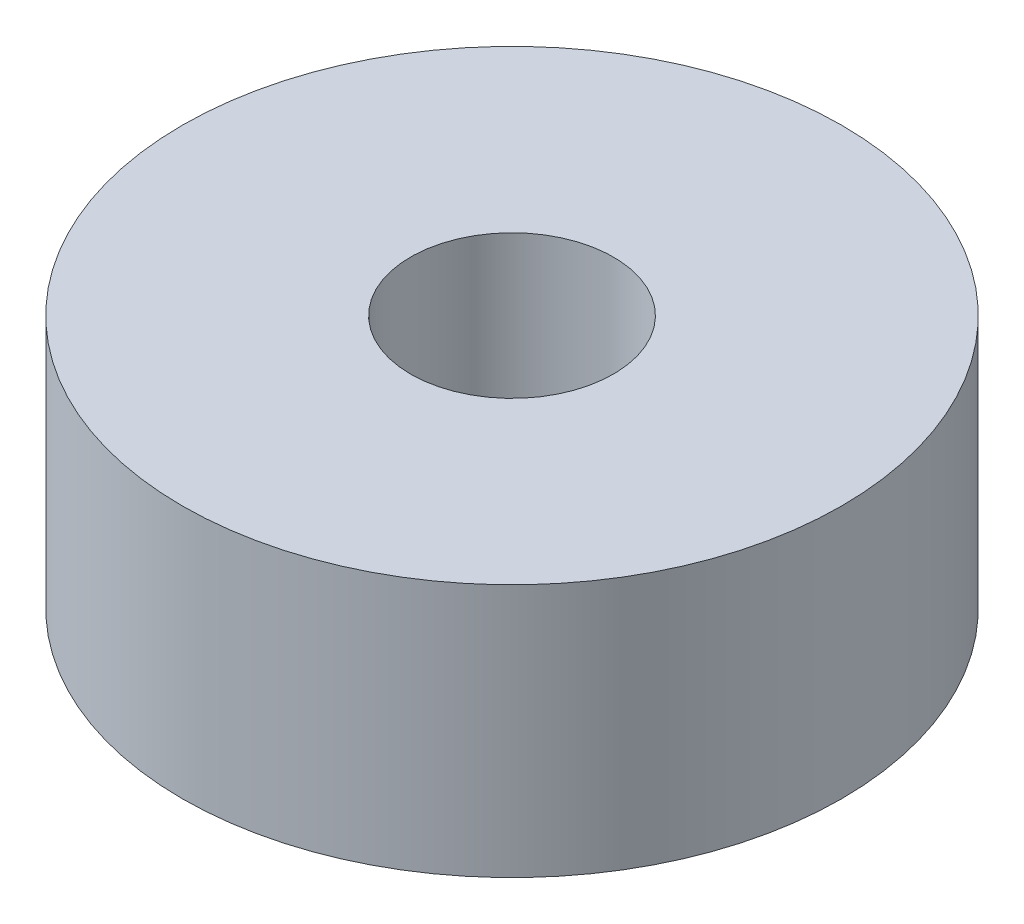
SolidWorks part; units mm, degrees
ref_plane "Plan de face" through (0, 0, 0) normal (0, 0, 1) x (1, 0, 0)
ref_plane "Plan de dessus" through (0, 0, 0) normal (0, 1, 0) x (1, 0, 0)
ref_plane "Plan de droite" through (0, 0, 0) normal (1, 0, 0) x (0, 0, -1)
sketch "Esquisse1" plane through (0, 0, 0) normal (0, 1, 0) x (1, 0, 0)
  circle A0 centre (0, 0) radius 2
  circle A1 centre (0, 0) radius 6.5
  dimension "D1" = 13
  dimension "D2" = 4
extrude "Boss.-Extru.1" add sketch "Esquisse1" along normal blind 5
